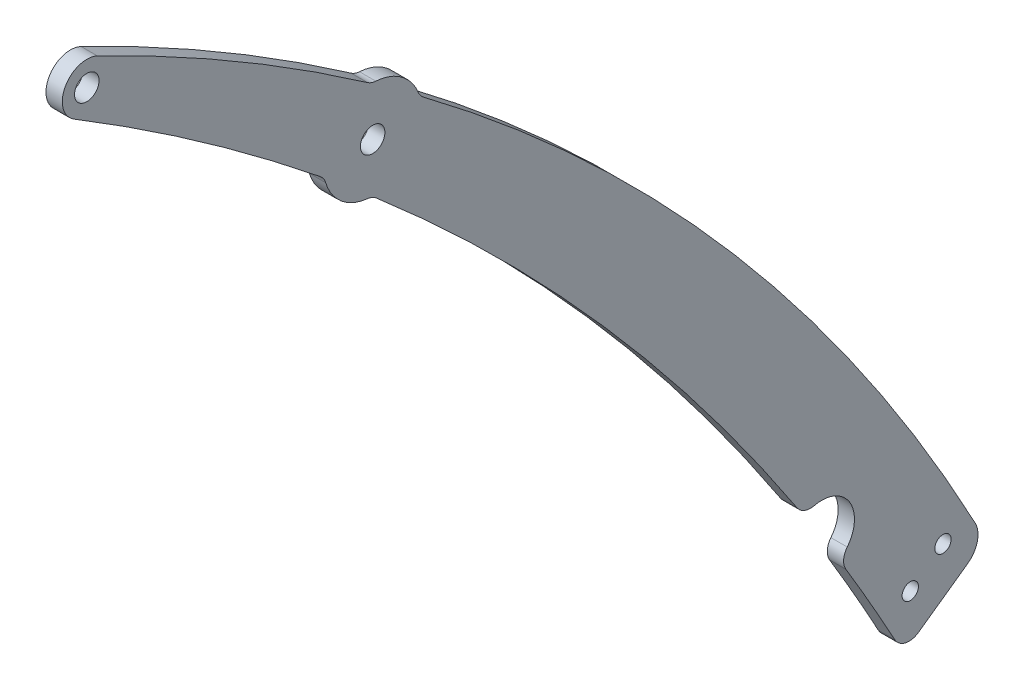
SolidWorks part; units mm, degrees
ref_plane "前视基准面" through (0, 0, 0) normal (0, 0, 1) x (1, 0, 0)
ref_plane "上视基准面" through (0, 0, 0) normal (0, 1, 0) x (1, 0, 0)
ref_plane "右视基准面" through (0, 0, 0) normal (1, 0, 0) x (0, 0, -1)
other "Configuration Table"
sketch "草图1" plane through (0, 0, 0) normal (1, 0, 0) x (0, 0, -1)
  line L0 (107.8637, -104.4041) -> (101.8458, -108.6865)
  arc A0 (1.3041, 2.7017) -> (-1.5587, -2.5633) centre (0, 0) ccw
  arc A1 (1.3041, 2.7017) -> (34.3734, -16.6567) centre (-103.0207, -213.4379) cw
  arc A2 (-1.5587, -2.5633) -> (28.5891, -23.732) centre (-147.0384, -241.8031) cw
  arc A3 (98.9293, -108.0126) -> (101.8458, -108.6865) centre (100.6863, -107.0569) ccw
  arc A4 (108.7717, -100.5487) -> (107.8637, -104.4041) centre (106.1243, -101.9598) cw
  circle A5 centre (100.8327, -103.8147) radius 1
  circle A6 centre (104.8327, -100.8147) radius 1
  arc A7 (89.0821, -88.8702) -> (93.1109, -95.2778) centre (90, -92.7634) cw
  arc A8 (92.9522, -97.5653) -> (98.9293, -108.0126) centre (-147.0384, -241.8031) cw
  arc A9 (93.1109, -95.2778) -> (92.9522, -97.5653) centre (94.6664, -96.535) ccw
  arc A10 (89.0821, -88.8702) -> (86.9518, -88.022) centre (88.6231, -86.9235) cw
  circle A11 centre (35, -23) radius 1.5
  circle A12 centre (0, 0) radius 1.5
  arc A13 (29.251, -24.7173) -> (34.3572, -28.9655) centre (35, -23) ccw
  arc A14 (40.569, -20.767) -> (35.3888, -17.0126) centre (35, -23) ccw
  arc A15 (41.2233, -21.6211) -> (108.7717, -100.5487) centre (-103.0207, -213.4379) cw
  arc A16 (35.4464, -29.4371) -> (86.9518, -88.022) centre (-147.0384, -241.8031) cw
  arc A17 (34.3734, -16.6567) -> (35.3888, -17.0126) centre (35.5184, -15.0168) ccw
  arc A18 (40.569, -20.767) -> (41.2233, -21.6211) centre (42.4253, -20.0226) ccw
  arc A19 (34.3572, -28.9655) -> (35.4464, -29.4371) centre (34.1429, -30.954) cw
  arc A20 (29.251, -24.7173) -> (28.5891, -23.732) centre (27.3347, -25.2897) ccw
  point P12 (100, -110)
  point P16 (110, -102.8839)
  point P24 (92.1049, -96.1648)
  point P38 (40.7423, -21.2603)
  point P41 (34.9361, -28.9997)
  dimension "D1" = 110
  dimension "D2" = 6
  dimension "D5" = 2
  dimension "D6" = 3
  dimension "D7" = 2
  dimension "D8" = 2
  dimension "D10" = 3
  dimension "D12" = 280
  dimension "D13" = 240
  dimension "D14" = 2
  dimension "D15" = 3
  dimension "D16" = 3
  dimension "D19" = 12
  dimension "D20" = 2
  dimension "D3" = 110
  dimension "D4" = 100
  dimension "D9" = 4
  dimension "D11" = 90
  dimension "D17" = 35
  dimension "D18" = 23
extrude "凸台-拉伸1" add sketch "草图1" along normal blind 2
